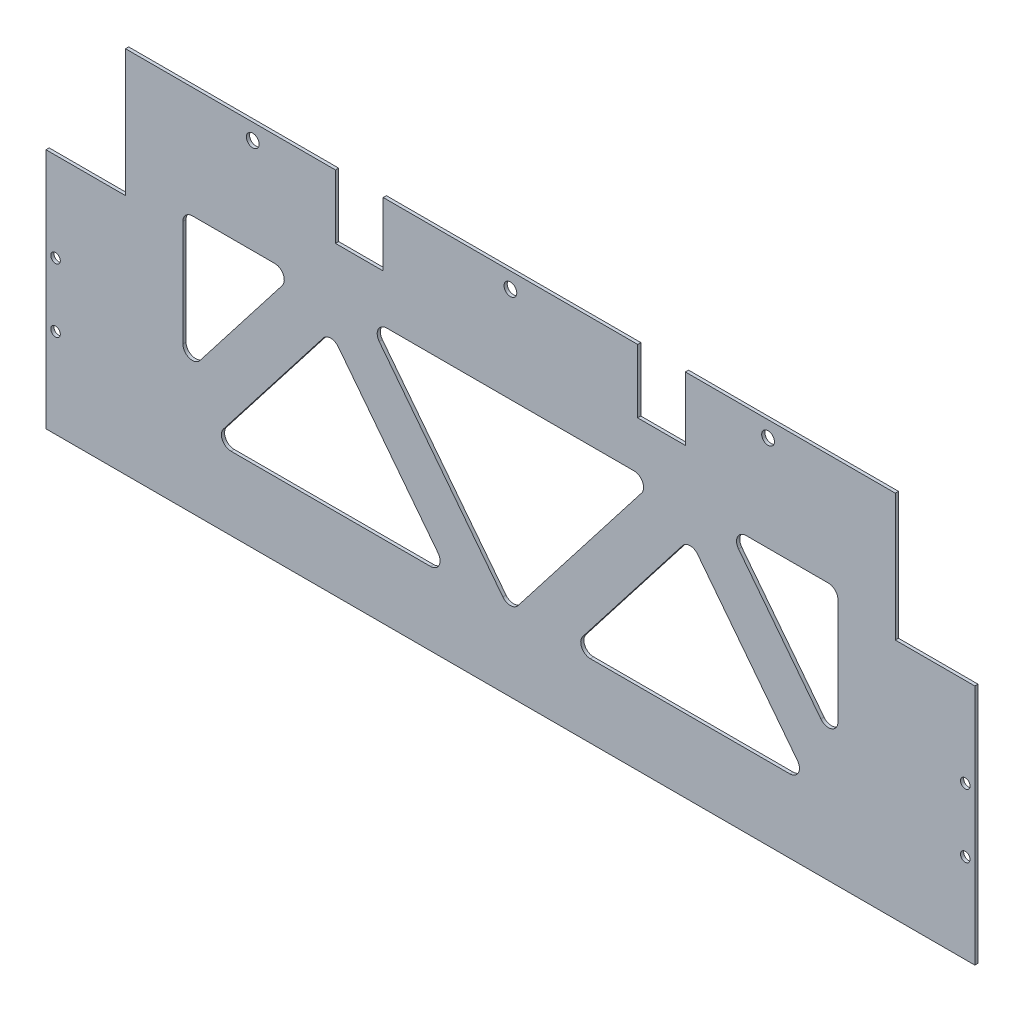
SolidWorks part; units mm, degrees
material "Thornel Mat VMA"
ref_plane "前视基准面" through (0, 0, 0) normal (0, 0, 1) x (1, 0, 0)
ref_plane "上视基准面" through (0, 0, 0) normal (0, 1, 0) x (1, 0, 0)
ref_plane "右视基准面" through (0, 0, 0) normal (1, 0, 0) x (0, 0, -1)
sketch "草图1" plane through (0, 0, 0) normal (0, 0, 1) x (1, 0, 0)
  line L0 (0, 0) -> (0, 76)
  line L1 (0, 76) -> (25, 76)
  line L2 (25, 76) -> (25, 116)
  line L3 (25, 116) -> (267, 116)
  line L4 (267, 116) -> (267, 76)
  line L5 (267, 76) -> (292, 76)
  line L6 (292, 76) -> (292, 0)
  line L7 (292, 0) -> (0, 0)
  line L8 (3, 48) -> (3, 28) construction
  line L9 (0, 38) -> (292, 38) construction
  line L10 (146, 116) -> (146, 0) construction
  line L11 (289, 48) -> (289, 28) construction
  circle A0 centre (3, 48) radius 1.5
  circle A1 centre (3, 28) radius 1.5
  circle A2 centre (289, 28) radius 1.5
  circle A3 centre (289, 48) radius 1.5
  point P13 (3, 38)
  dimension "D7" = 3
  dimension "D1" = 292
  dimension "D2" = 76
  dimension "D3" = 40
  dimension "D4" = 25
  dimension "D5" = 20
  dimension "D6" = 3
extrude "凸台-拉伸1" add sketch "草图1" along normal blind 1
sketch "草图2" plane through (0, 0, 1) normal (0, 0, 1) x (1, 0, 0)
  line L0 (146, 116) -> (146, 0) construction
  line L1 (267, 116) -> (25, 116) construction
  line L2 (0, 0) -> (292, 0) construction
  line L3 (186, 116) -> (186, 96)
  line L4 (91, 116) -> (106, 116)
  line L5 (91, 116) -> (91, 96)
  line L6 (91, 96) -> (106, 96)
  line L7 (106, 116) -> (106, 96)
  line L8 (201, 96) -> (186, 96)
  line L9 (201, 116) -> (201, 96)
  line L10 (201, 116) -> (186, 116)
  line L11 (25, 116) -> (25, 76) construction
  circle A0 centre (65, 111) radius 2
  circle A1 centre (227, 111) radius 2
  circle A2 centre (146, 111) radius 2
  point P14 (98.5, 116)
  point P15 (193.5, 116)
  dimension "D4" = 4
  dimension "D7" = 4
  dimension "D1" = 95
  dimension "D2" = 15
  dimension "D3" = 20
  dimension "D5" = 5
  dimension "D6" = 40
extrude "切除-拉伸1" cut sketch "草图2" against normal through all
sketch "草图3" plane through (0, 0, 0) normal (0, 0, -1) x (-1, 0, 0)
  line L0 (-146, 116) -> (-146, 0) construction
  line L1 (-186, 116) -> (-106, 116) construction
  line L2 (0, 0) -> (-292, 0) construction
  line L3 (-191, 81) -> (-101, 81)
  line L4 (-101, 81) -> (-146, 23)
  line L5 (-146, 23) -> (-146, 81)
  line L6 (-89.5147, 71.3333) -> (-127.0147, 23)
  line L7 (-127.0147, 23) -> (-52.0147, 23)
  line L8 (-52.0147, 23) -> (-89.5147, 71.3333)
  line L9 (-78.0294, 81) -> (-43.0294, 81)
  line L10 (-43.0294, 81) -> (-43.0294, 35.8889)
  line L11 (-43.0294, 35.8889) -> (-78.0294, 81)
  line L12 (-248.9706, 35.8889) -> (-213.9706, 81)
  line L13 (-248.9706, 81) -> (-248.9706, 35.8889)
  line L14 (-213.9706, 81) -> (-248.9706, 81)
  line L15 (-239.9853, 23) -> (-202.4853, 71.3333)
  line L16 (-164.9853, 23) -> (-239.9853, 23)
  line L17 (-202.4853, 71.3333) -> (-164.9853, 23)
  line L18 (-191, 81) -> (-146, 23)
  dimension "D1" = 35
  dimension "D2" = 58
  dimension "D3" = 45
  dimension "D4" = 15
  dimension "D5" = 75
  dimension "D6" = 15
  dimension "D7" = 35
extrude "切除-拉伸2" cut sketch "草图3" against normal up to next contours L11 L10 L9 | L7 L8 L6 | L5 L4 L3 | L17 L15 L16 | L3 L18 L5 | L12 L14 L13
fillet "圆角1" radius 3 15 edges at (101, 81, 0.5) (127.0147, 23, 0.5) (52.0147, 23, 0.5) (89.5147, 71.3333, 0.5) (43.0294, 35.8889, 0.5) (78.0294, 81, 0.5) (43.0294, 81, 0.5) (248.9706, 35.8889, 0.5) (248.9706, 81, 0.5) (213.9706, 81, 0.5) (239.9853, 23, 0.5) (164.9853, 23, 0.5) (202.4853, 71.3333, 0.5) (146, 23, 0.5) (191, 81, 0.5)
